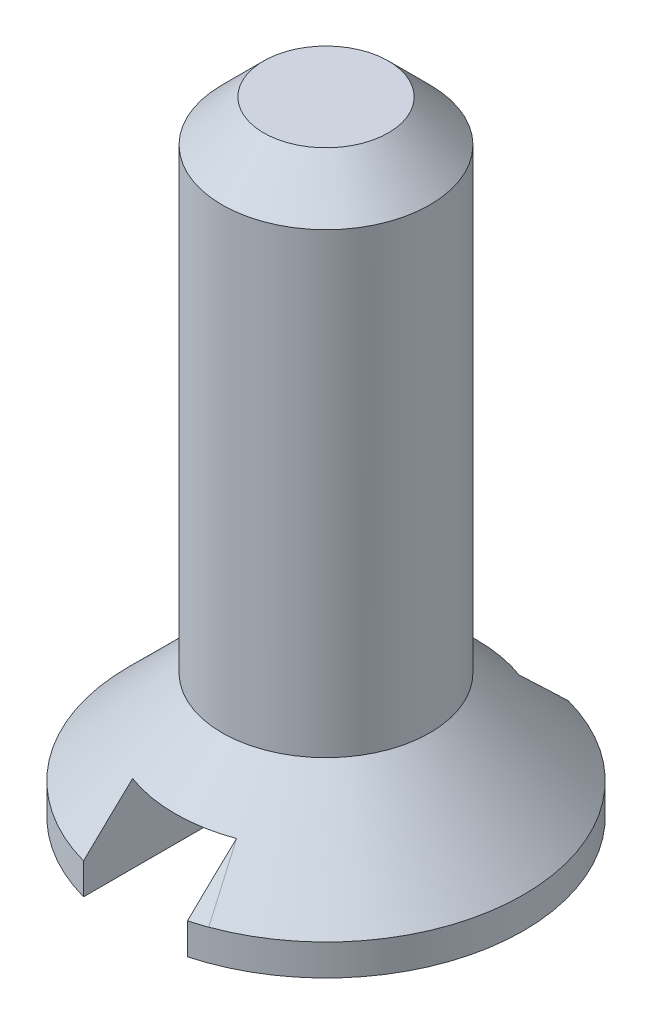
SolidWorks part; units mm, degrees
ref_plane "Спереди" through (0, 0, 0) normal (0, 0, 1) x (1, 0, 0)
ref_plane "Сверху" through (0, 0, 0) normal (0, 1, 0) x (1, 0, 0)
ref_plane "Справа" through (0, 0, 0) normal (1, 0, 0) x (0, 0, -1)
sketch "Эскиз1" plane through (0, 0, 0) normal (0, 0, 1) x (1, 0, 0)
  line L0 (0, 0) -> (-1.9, 0)
  line L1 (-1.9, 0) -> (-1.9, 0.3)
  line L2 (-1.9, 0.3) -> (-1, 1.2)
  line L3 (-1, 1.2) -> (-1, 6)
  line L4 (-1, 6) -> (0, 6)
  line L5 (0, 6) -> (0, 0)
  line L6 (-1, 1.2) -> (0, 1.2) construction
  dimension "D1" = 6
  dimension "D2" = 1.9
  dimension "D3" = 1
  dimension "D4" = 45
  dimension "D5" = 1.2
revolve "Повернуть1" add sketch "Эскиз1" angle 360 about L5
sketch "Эскиз2" plane through (0, 0, 0) normal (0, 0, 1) x (1, 0, 0)
  line L0 (-1.9, 0) -> (1.9, 0) construction
  line L1 (-0.5, 0) -> (0.5, 0)
  line L2 (-0.5, 0) -> (-0.5, 0.75)
  line L3 (-0.5, 0.75) -> (0.5, 0.75)
  line L4 (0.5, 0) -> (0.5, 0.75)
  dimension "D1" = 0.75
  dimension "D2" = 1
extrude "Вырез-Вытянуть1" cut sketch "Эскиз2" against normal mid plane 20
chamfer "Фаска1" distance 0.4 angle 45 1 edges at (-1, 6, 0)
